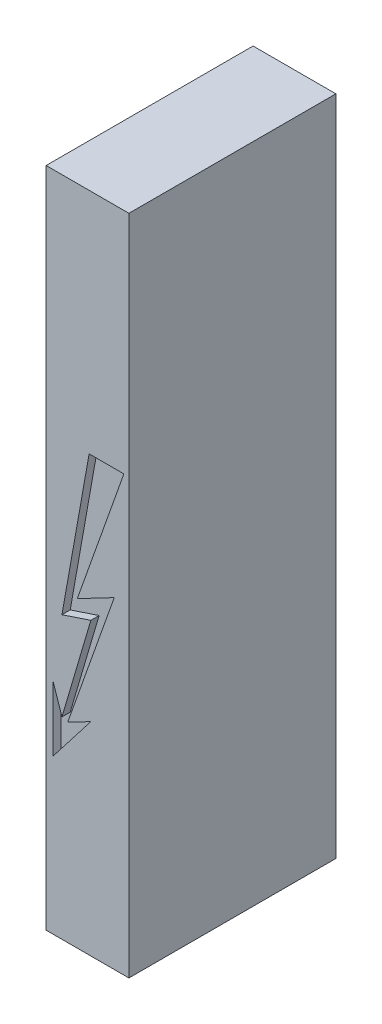
SolidWorks part; units mm, degrees
ref_plane "Front Plane" through (0, 0, 0) normal (0, 0, 1) x (1, 0, 0)
ref_plane "Top Plane" through (0, 0, 0) normal (0, 1, 0) x (1, 0, 0)
ref_plane "Right Plane" through (0, 0, 0) normal (1, 0, 0) x (0, 0, -1)
sketch "Sketch1" plane through (0, 0, 0) normal (0, 0, 1) x (1, 0, 0)
  line L1 (5, -40) -> (-5, -40)
  line L2 (5, -40) -> (5, 40)
  line L3 (5, 40) -> (-5, 40)
  line L4 (-5, -40) -> (-5, 40)
  line L5 (5, -40) -> (-5, 40) construction
  line L6 (5, 40) -> (-5, -40) construction
  point P0 (0, 0)
  dimension "D1" = 10
  dimension "D2" = 80
extrude "Boss-Extrude1" add sketch "Sketch1" along normal mid plane 25
sketch "Sketch2" plane through (0, 0, 12.5) normal (0, 0, 1) x (1, 0, 0)
  line L0 (0.1932, 12.431) -> (-3.0909, -6.0421)
  line L1 (-3.0909, -6.0421) -> (0.4031, -4.8775)
  line L2 (0.4031, -4.8775) -> (-3.0909, -16.736)
  line L3 (-3.0909, -16.736) -> (-4.1942, -13.4263)
  line L4 (-4.1942, -13.4263) -> (-4.1942, -21.4122)
  line L5 (-4.1942, -21.4122) -> (0.4031, -15.476)
  line L6 (0.4031, -15.476) -> (-2.3955, -16.9409)
  line L7 (-2.3955, -16.9409) -> (3.2269, -1.0941)
  line L8 (3.2269, -1.0941) -> (-1.238, -3.4313)
  line L9 (-1.238, -3.4313) -> (4.3899, 12.431)
  line L10 (4.3899, 12.431) -> (0.1932, 12.431)
extrude "Cut-Extrude1" cut sketch "Sketch2" against normal blind 1 contours L10 L0 L1 L2 L3 L4 L5 L6 L7 L8 L9
